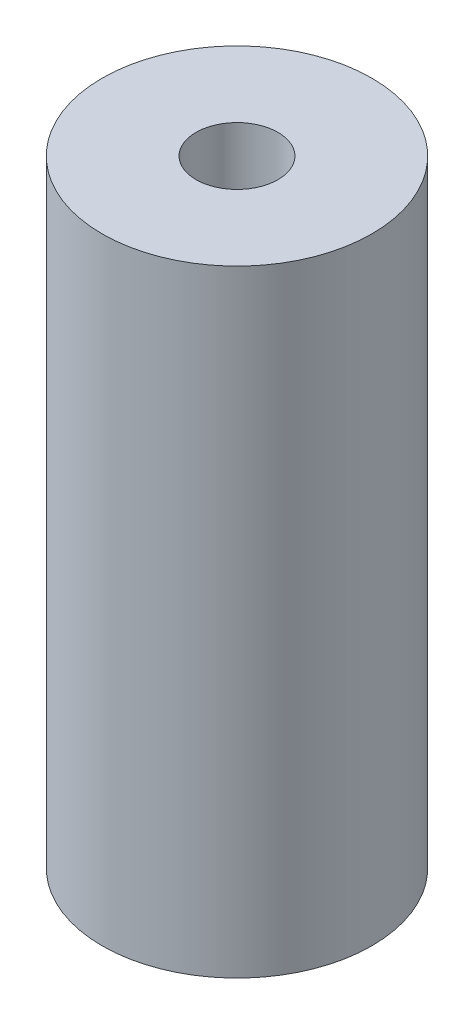
SolidWorks part; units mm, degrees
ref_plane "Front Plane" through (0, 0, 0) normal (0, 0, 1) x (1, 0, 0)
ref_plane "Top Plane" through (0, 0, 0) normal (0, 1, 0) x (1, 0, 0)
ref_plane "Right Plane" through (0, 0, 0) normal (1, 0, 0) x (0, 0, -1)
sketch "Sketch1" plane through (0, 0, 0) normal (0, 1, 0) x (1, 0, 0)
  circle A0 centre (0, 0) radius 11.1125
  circle A1 centre (0, 0) radius 3.3782
  dimension "D1" = 22.225
  dimension "D2" = 6.7564
extrude "Boss-Extrude1" add sketch "Sketch1" along normal blind 50.8
